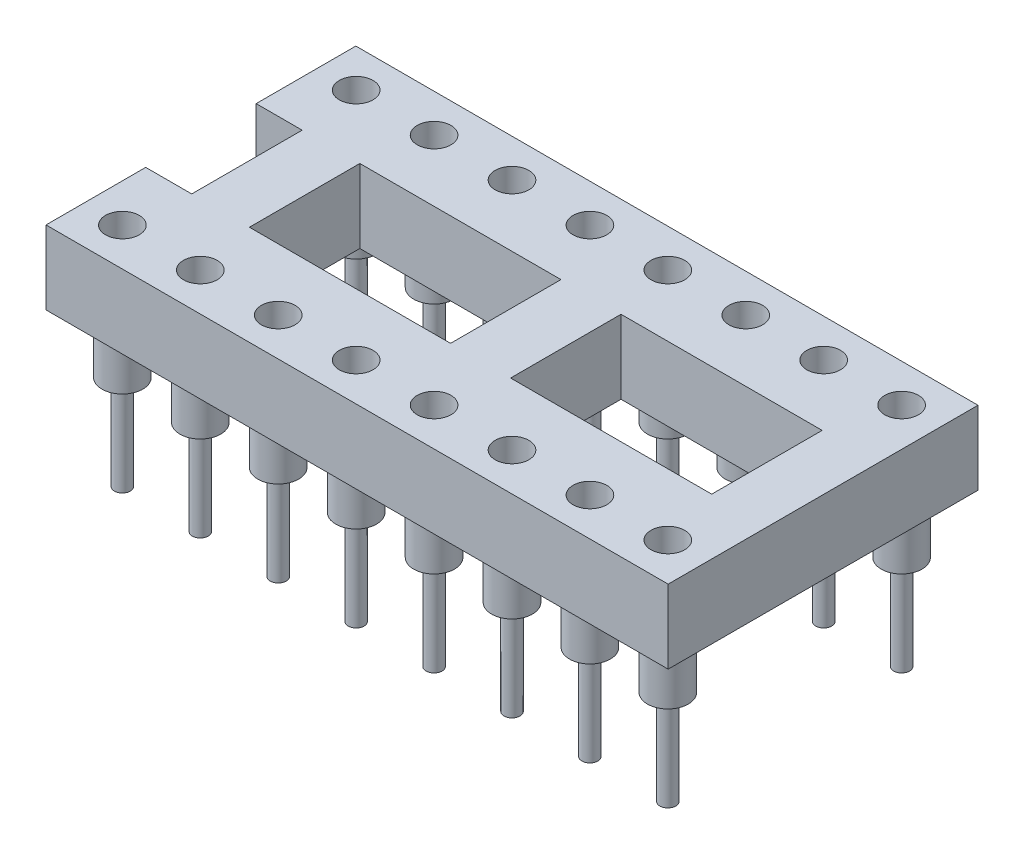
SolidWorks part; units mm, degrees
ref_plane "Front Plane" through (0, 0, 0) normal (0, 0, 1) x (1, 0, 0)
ref_plane "Top Plane" through (0, 0, 0) normal (0, 1, 0) x (1, 0, 0)
ref_plane "Right Plane" through (0, 0, 0) normal (1, 0, 0) x (0, 0, -1)
sketch "Sketch1" plane through (0, 0, 0) normal (0, 1, 0) x (1, 0, 0)
  line L0 (10.14, 2.8832) -> (10.14, -2.1793)
  line L1 (-10.14, 5.05) -> (10.14, 5.05)
  line L2 (-10.14, 5.05) -> (-10.14, 1.8)
  line L3 (-10.14, 1.8) -> (-8.64, 1.8)
  line L4 (10.14, 5.05) -> (10.14, 2.8832)
  line L5 (-10.14, 5.05) -> (10.14, 2.8832) construction
  line L6 (-10.14, 1.8) -> (10.14, 5.05) construction
  line L7 (10.14, -5.05) -> (-10.14, -5.05)
  line L8 (10.14, -5.05) -> (10.14, -2.1793)
  line L9 (8.31, -1.8) -> (1.7539, -1.8)
  line L10 (-10.14, -5.05) -> (-10.14, -1.8)
  line L11 (10.14, -5.05) -> (-10.14, -1.8) construction
  line L12 (10.14, -2.1793) -> (-10.14, -5.05) construction
  line L13 (8.31, 1.8) -> (8.31, -1.8)
  line L14 (-0.2039, 1.8) -> (-0.2039, -1.8)
  line L15 (1.7539, -1.8) -> (1.7539, 1.8)
  line L16 (-8.64, 1.8) -> (-8.64, -1.8)
  line L17 (-6.76, 1.8) -> (-6.76, -1.8)
  line L18 (-0.2039, 0) -> (1.7539, 0) construction
  line L19 (-6.76, 1.8) -> (-0.2039, 1.8)
  line L20 (-8.64, -1.8) -> (-10.14, -1.8)
  line L21 (1.7539, 1.8) -> (8.31, 1.8)
  line L22 (-0.2039, -1.8) -> (-6.76, -1.8)
  line L23 (0, -5.05) -> (0, 5.05) construction
  point P0 (2.0278, 3.75)
  point P5 (0.6284, -3.5257)
  point P25 (1.7539, 1.8)
  dimension "D1" = 10.1
  dimension "D2" = 20.28
  dimension "D3" = 1.83
  dimension "D5" = 1.88
  dimension "D6" = 1.5
  dimension "D7" = 3.25
extrude "Boss-Extrude1" add sketch "Sketch1" along normal blind 2.4 contours L2 L3 L16 L20 L10 L7 L8 L0 L4 L1
sketch "Sketch2" plane through (0, 2.4, 0) normal (0, 1, 0) x (1, 0, 0)
  line L0 (0, 0) -> (-8.89, 0) construction
  line L1 (-8.89, 0) -> (-8.89, -3.81) construction
  circle A0 centre (-8.89, -3.81) radius 0.55
  dimension "D3" = 1.1
  dimension "D1" = 3.81
  dimension "D2" = 8.89
extrude "Cut-Extrude1" cut sketch "Sketch2" against normal blind 2 contours A0
ref_plane "Plane1" through (0, 0, 3.81) normal (0, 0, 1) x (1, 0, 0)
sketch "Sketch3" plane through (0, 0, 3.81) normal (0, 0, 1) x (1, 0, 0)
  line L0 (-9.555, 0) -> (-9.555, -1.9)
  line L1 (-9.555, -1.9) -> (-9.15, -1.9)
  line L2 (-9.15, -1.9) -> (-9.15, -4.98)
  line L3 (-9.15, -4.98) -> (-8.89, -4.98)
  line L4 (-8.89, -4.98) -> (-8.89, 0)
  line L5 (-8.89, 0) -> (-9.555, 0)
  line L6 (-8.89, 0) -> (-8.89, 2.4) construction
  line L7 (-10.14, 0) -> (10.14, 0) construction
  line L8 (-10.14, 2.4) -> (10.14, 2.4) construction
  point P4 (0, 0)
  dimension "D1" = 0.665
  dimension "D2" = 0.26
  dimension "D3" = 4.3
  dimension "D4" = 7.38
revolve "Revolve1" add sketch "Sketch3" angle 360 about L6
pattern_linear "LPattern1" count 8 spacing 2.54 along (1, 0, 0) count 2 spacing 7.62 along (0, 0, -1) of "Revolve1", "Cut-Extrude1"
